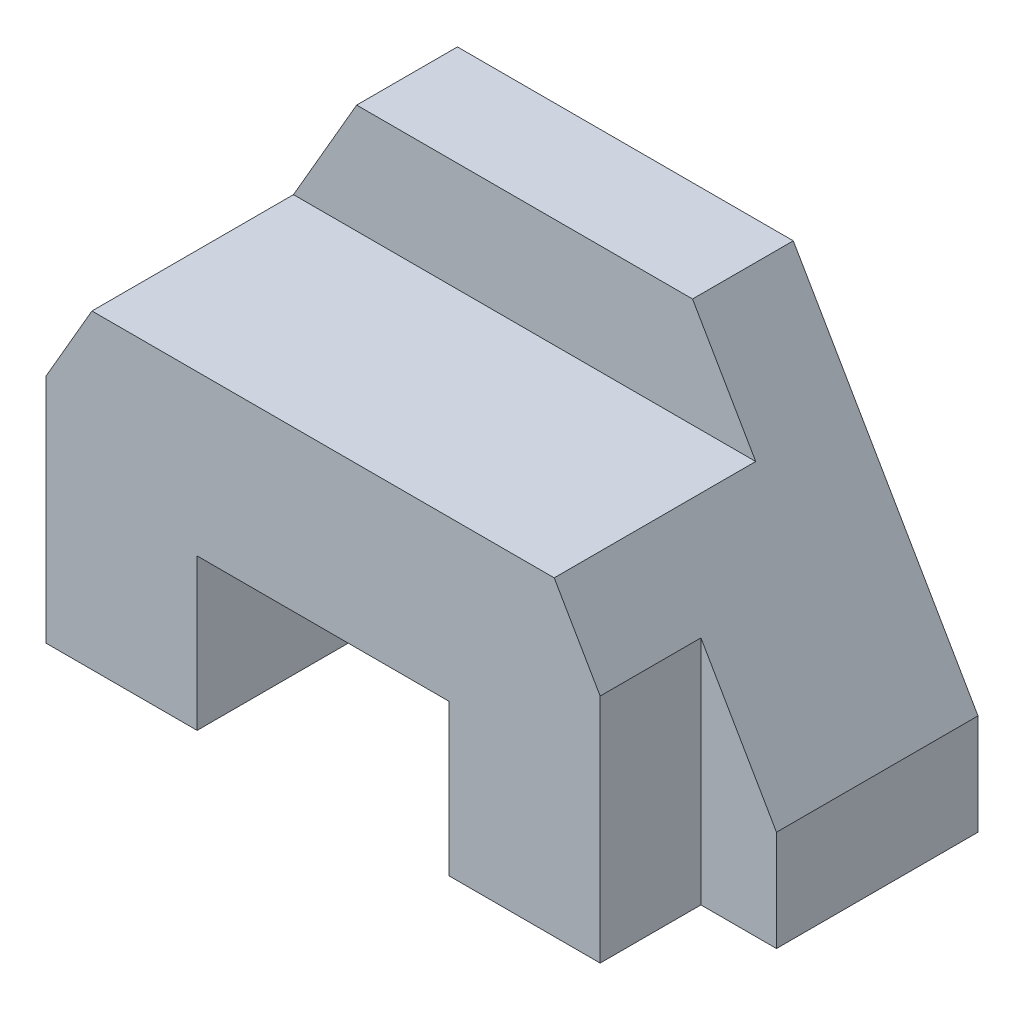
SolidWorks part; units mm, degrees
ref_plane "Front Plane" through (0, 0, 0) normal (0, 0, 1) x (1, 0, 0)
ref_plane "Top Plane" through (0, 0, 0) normal (0, 1, 0) x (1, 0, 0)
ref_plane "Right Plane" through (0, 0, 0) normal (1, 0, 0) x (0, 0, -1)
sketch "Sketch1" plane through (0, 0, 0) normal (0, 0, 1) x (1, 0, 0)
  line L0 (-381, 0) -> (-381, 457.2)
  line L1 (55, 0) -> (-55, 0) construction
  line L2 (-381, 457.2) -> (381, 457.2)
  line L3 (381, 457.2) -> (381, 0)
  line L4 (0, -55) -> (0, 55) construction
  line L5 (381, 0) -> (1066.8, 0)
  line L6 (1066.8, 0) -> (1066.8, 304.8)
  line L7 (1066.8, 304.8) -> (508, 1270)
  line L8 (508, 1270) -> (-508, 1270)
  line L9 (-508, 1270) -> (-1066.8, 304.8)
  line L10 (-1066.8, 304.8) -> (-1066.8, 0)
  line L11 (-1066.8, 0) -> (-381, 0)
  point P5 (0, 457.2)
  point P9 (0, 1270)
  dimension "D1" = 762
  dimension "D2" = 457.2
  dimension "D3" = 304.8
  dimension "D4" = 1270
  dimension "D5" = 1016
  dimension "D6" = 2133.6
extrude "Boss-Extrude1" add sketch "Sketch1" against normal blind 914.4
sketch "Sketch2" plane through (0, 0, 0) normal (0, 1, 0) x (1, 0, 0)
  line L0 (-1066.8, 304.8) -> (-838.2, 304.8)
  line L1 (-1066.8, 914.4) -> (-1066.8, 0) construction
  line L2 (-838.2, 304.8) -> (-838.2, 0)
  line L4 (1066.8, 304.8) -> (838.2, 304.8)
  line L6 (838.2, 304.8) -> (838.2, 0)
  line L7 (1066.8, 0) -> (508, 0) construction
  line L8 (1066.8, 914.4) -> (1066.8, 0) construction
  line L9 (-508, 914.4) -> (-1066.8, 914.4) construction
  line L10 (-508, 0) -> (-1066.8, 0) construction
  line L11 (1066.8, 304.8) -> (1066.8, 0)
  line L12 (1066.8, 0) -> (838.2, 0)
  line L13 (-838.2, 0) -> (-1066.8, 0)
  line L14 (-1066.8, 0) -> (-1066.8, 304.8)
  dimension "D1" = 1676.4
  dimension "D2" = 609.6
extrude "Cut-Extrude1" cut sketch "Sketch2" along normal through all
sketch "Sketch3" plane through (0, 0, 0) normal (1, 0, 0) x (0, 0, -1)
  line L0 (609.6, 1270) -> (609.6, 939.8)
  line L1 (914.4, 1270) -> (0, 1270) construction
  line L2 (609.6, 939.8) -> (0, 939.8)
  line L3 (0, 1270) -> (0, 699.6545) construction
  line L4 (914.4, 1270) -> (914.4, 304.8) construction
  line L6 (502.92, 0) -> (-502.92, 0) construction
  line L7 (609.6, 1270) -> (0, 1270)
  line L8 (0, 1270) -> (0, 939.8)
  dimension "D1" = 304.8
  dimension "D2" = 939.8
extrude "Cut-Extrude2" cut sketch "Sketch3" against normal through all both and the other way through all
